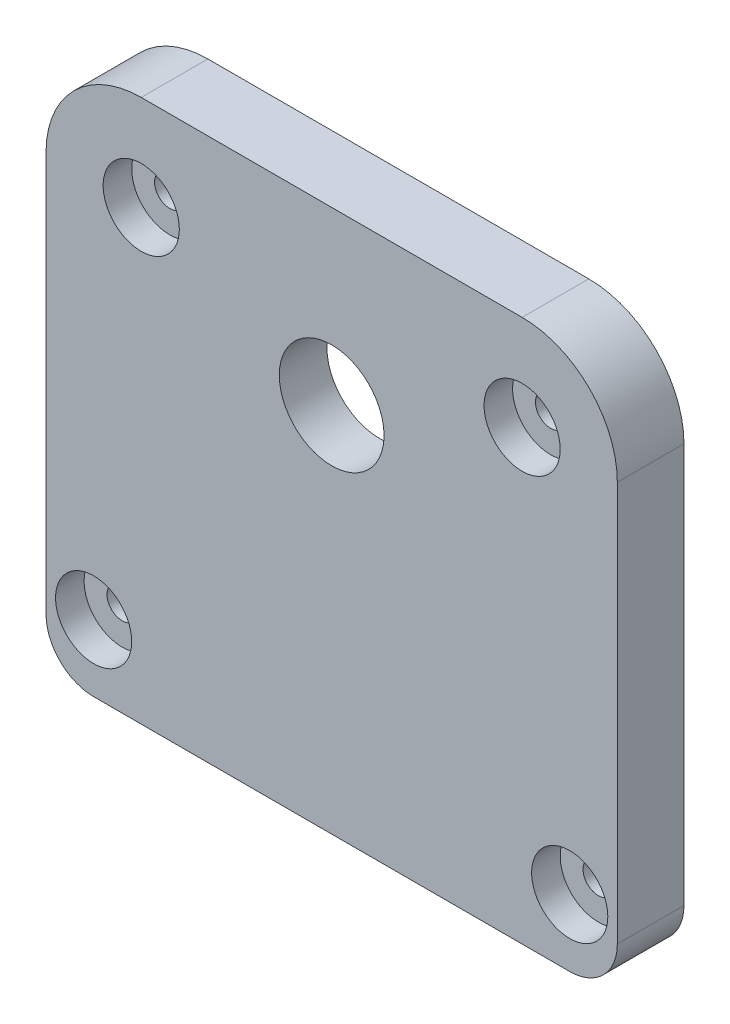
SolidWorks part; units mm, degrees
ref_plane "前视基准面" through (0, 0, 0) normal (0, 0, 1) x (1, 0, 0)
ref_plane "上视基准面" through (0, 0, 0) normal (0, 1, 0) x (1, 0, 0)
ref_plane "右视基准面" through (0, 0, 0) normal (1, 0, 0) x (0, 0, -1)
other "Configuration Table"
sketch "草图1" plane through (0, 0, 0) normal (0, 0, 1) x (1, 0, 0)
  line L1 (-30, -25) -> (30, -25)
  line L2 (-30, -25) -> (-30, 25)
  line L3 (-30, 25) -> (30, 25)
  line L4 (30, -25) -> (30, 25)
  line L5 (-30, -25) -> (30, 25) construction
  line L6 (-30, 25) -> (30, -25) construction
  circle A0 centre (0, 0) radius 15
  point P0 (0, 0)
  dimension "D3" = 30
  dimension "D1" = 60
  dimension "D2" = 50
extrude "凸台-拉伸5" add sketch "草图1" along normal blind 5
sketch "草图4" plane through (0, 0, 5) normal (0, 0, 1) x (1, 0, 0)
  line L1 (-30, -25) -> (30, -25)
  line L2 (-30, -25) -> (-30, 25)
  line L3 (-30, 25) -> (30, 25)
  line L4 (30, -25) -> (30, 25)
  line L5 (-30, -25) -> (30, 25) construction
  line L6 (-30, 25) -> (30, -25) construction
  circle A0 centre (0, 0) radius 5.5
  dimension "D1" = 11
extrude "凸台-拉伸6" add sketch "草图4" along normal blind 5
sketch "草图5" plane through (0, 0, 0) normal (0, 0, -1) x (-1, 0, 0)
  circle A0 centre (-20, 22) radius 1.6
  circle A1 centre (-25, -18) radius 1.6
  circle A2 centre (20, 22) radius 1.6
  circle A3 centre (25, -18) radius 1.6
extrude "切除-拉伸1" cut sketch "草图5" against normal blind 10
sketch "草图6" plane through (0, 25, 0) normal (0, 1, 0) x (1, 0, 0)
  line L1 (-30, -10) -> (30, -10)
  line L2 (-30, -10) -> (-30, 0)
  line L3 (-30, 0) -> (30, 0)
  line L4 (30, -10) -> (30, 0)
extrude "凸台-拉伸7" add sketch "草图6" along normal blind 7
fillet "圆角3" radius 10 1 edges at (-30, 32, 5)
sketch "草图7" plane through (0, 0, 10) normal (0, 0, 1) x (1, 0, 0)
  circle A0 centre (-20, 22) radius 4
  circle A1 centre (20, 22) radius 4
  circle A2 centre (-25, -18) radius 4
  circle A3 centre (25, -18) radius 4
  dimension "D1" = 8
  dimension "D2" = 8
  dimension "D3" = 8
  dimension "D4" = 8
fillet "圆角5" radius 10 1 edges at (30, 32, 5)
fillet "圆角6" radius 5 1 edges at (-30, -25, 5)
fillet "圆角7" radius 5 1 edges at (30, -25, 5)
sketch "草图8" plane through (0, 0, 0) normal (0, 0, -1) x (-1, 0, 0)
  circle A0 centre (0, 0) radius 41.9849
extrude "切除-拉伸3" cut sketch "草图8" against normal blind 3
extrude "切除-拉伸4" cut sketch "草图7" against normal blind 3
sketch "草图9" plane through (0, 0, 3) normal (0, 0, -1) x (-1, 0, 0)
  circle A0 centre (0, 0) radius 15
extrude "凸台-拉伸8" add sketch "草图9" against normal blind 7
sketch "草图10" plane through (0, 0, 3) normal (0, 0, -1) x (-1, 0, 0)
  line L0 (0, 0) -> (0, 14)
  circle A0 centre (0, 14) radius 15
  dimension "D2" = 30
  dimension "D1" = 14
extrude "切除-拉伸5" cut sketch "草图10" against normal blind 2
sketch "草图11" plane through (0, 0, 5) normal (0, 0, -1) x (-1, 0, 0)
  circle A0 centre (0, 14) radius 5.5
  dimension "D1" = 11
extrude "切除-拉伸6" cut sketch "草图11" against normal through all
